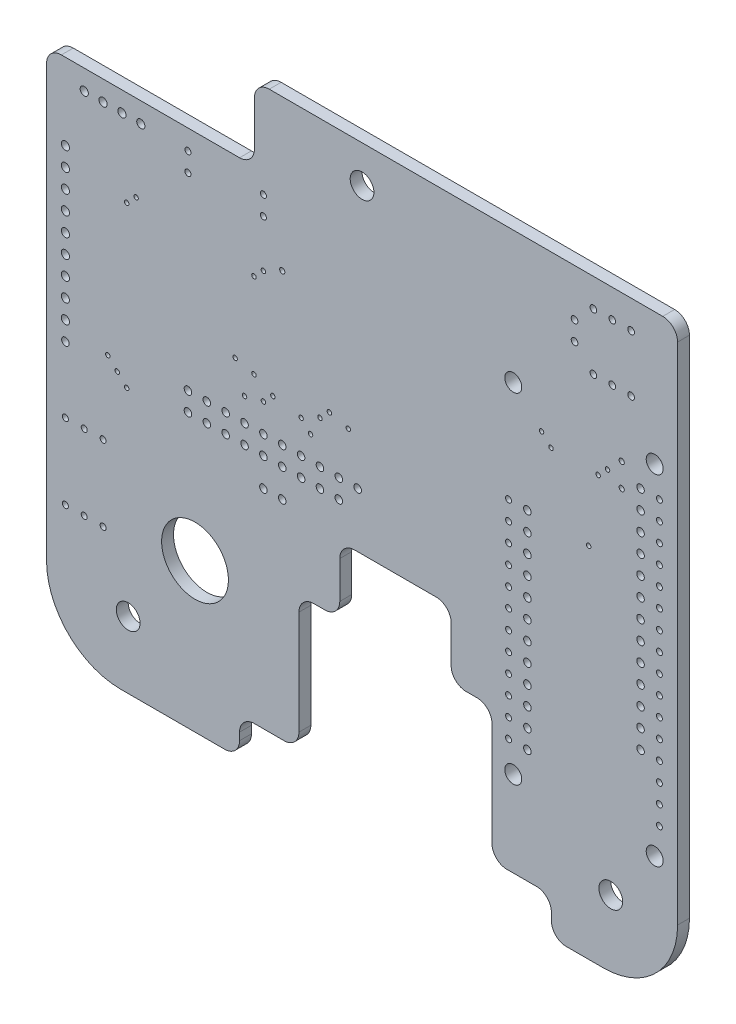
SolidWorks part; units mm, degrees
material "ABS PC"
ref_plane "Front Plane" through (0, 0, 0) normal (0, 0, 1) x (1, 0, 0)
ref_plane "Top Plane" through (0, 0, 0) normal (0, 1, 0) x (1, 0, 0)
ref_plane "Right Plane" through (0, 0, 0) normal (1, 0, 0) x (0, 0, -1)
sketch "20" plane through (0, 0, 0) normal (0, 0, 1) x (1, 0, 0)
  line L0 (28, 72) -> (28, 78)
  line L1 (85, 78) -> (85, 10)
  line L2 (68, 2) -> (68, 3)
  line L3 (66, 5) -> (62, 5)
  line L4 (60, 7) -> (60, 21)
  line L5 (56.5, 23) -> (58, 23)
  line L6 (54.5, 30) -> (54.5, 25)
  line L7 (52.5, 32) -> (41.5, 32)
  line L8 (39.5, 30) -> (39.5, 25)
  line L9 (37.5, 23) -> (36, 23)
  line L10 (34, 21) -> (34, 7)
  line L11 (32, 5) -> (28, 5)
  line L12 (26, 3) -> (26, 2)
  line L13 (0, 68) -> (0, 10)
  line L14 (2, 70) -> (26, 70)
  line L15 (83, 80) -> (30, 80)
  line L16 (10, 0) -> (24, 0)
  line L17 (70, 0) -> (75, 0)
  arc A0 (26, 70) -> (28, 72) centre (26, 72) ccw
  arc A1 (30, 80) -> (28, 78) centre (30, 78) ccw
  arc A2 (85, 78) -> (83, 80) centre (83, 78) ccw
  arc A3 (75, 0) -> (85, 10) centre (75, 10) ccw
  arc A4 (68, 2) -> (70, 0) centre (70, 2) ccw
  arc A5 (68, 3) -> (66, 5) centre (66, 3) ccw
  arc A6 (60, 7) -> (62, 5) centre (62, 7) ccw
  arc A7 (60, 21) -> (58, 23) centre (58, 21) ccw
  arc A8 (54.5, 25) -> (56.5, 23) centre (56.5, 25) ccw
  arc A9 (54.5, 30) -> (52.5, 32) centre (52.5, 30) ccw
  arc A10 (41.5, 32) -> (39.5, 30) centre (41.5, 30) ccw
  arc A11 (37.5, 23) -> (39.5, 25) centre (37.5, 25) ccw
  arc A12 (36, 23) -> (34, 21) centre (36, 21) ccw
  arc A13 (32, 5) -> (34, 7) centre (32, 7) ccw
  arc A14 (28, 5) -> (26, 3) centre (28, 3) ccw
  arc A15 (24, 0) -> (26, 2) centre (24, 2) ccw
  arc A16 (0, 10) -> (10, 0) centre (10, 10) ccw
  arc A17 (2, 70) -> (0, 68) centre (2, 68) ccw
  circle A18 centre (42.5, 75) radius 1.6
  circle A19 centre (11, 9) radius 1.6
  circle A20 centre (76, 9) radius 1.6
  circle A21 centre (62.865, 62.23) radius 1.143
  circle A22 centre (62.865, 16.51) radius 1.143
  circle A23 centre (81.915, 16.51) radius 1.143
  circle A24 centre (81.915, 62.23) radius 1.143
  circle A25 centre (11, 9) radius 0.8 construction
  circle A26 centre (76, 9) radius 0.8 construction
  circle A27 centre (20, 20) radius 4.5
sketch "44" plane through (0, 0, 0) normal (0, 0, 1) x (1, 0, 0)
  circle A0 centre (31.75, 33.02) radius 0.508
  circle A1 centre (29.21, 33.02) radius 0.508
  circle A2 centre (41.91, 39.37) radius 0.508
  circle A3 centre (2.54, 36.83) radius 0.508
  circle A4 centre (80.01, 58.42) radius 0.508
  circle A5 centre (80.01, 27.94) radius 0.508
  circle A6 centre (80.01, 30.48) radius 0.508
  circle A7 centre (80.01, 33.02) radius 0.508
  circle A8 centre (80.01, 35.56) radius 0.508
  circle A9 centre (80.01, 38.1) radius 0.508
  circle A10 centre (80.01, 40.64) radius 0.508
  circle A11 centre (80.01, 43.18) radius 0.508
  circle A12 centre (80.01, 45.72) radius 0.508
  circle A13 centre (80.01, 48.26) radius 0.508
  circle A14 centre (80.01, 50.8) radius 0.508
  circle A15 centre (80.01, 53.34) radius 0.508
  circle A16 centre (80.01, 55.88) radius 0.508
  circle A17 centre (64.77, 48.26) radius 0.508
  circle A18 centre (64.77, 45.72) radius 0.508
  circle A19 centre (64.77, 43.18) radius 0.508
  circle A20 centre (64.77, 40.64) radius 0.508
  circle A21 centre (64.77, 38.1) radius 0.508
  circle A22 centre (64.77, 35.56) radius 0.508
  circle A23 centre (64.77, 33.02) radius 0.508
  circle A24 centre (64.77, 30.48) radius 0.508
  circle A25 centre (64.77, 27.94) radius 0.508
  circle A26 centre (64.77, 25.4) radius 0.508
  circle A27 centre (64.77, 22.86) radius 0.508
  circle A28 centre (64.77, 20.32) radius 0.508
  circle A29 centre (19.05, 36.83) radius 0.508
  circle A30 centre (19.05, 39.37) radius 0.508
  circle A31 centre (21.59, 36.83) radius 0.508
  circle A32 centre (21.59, 39.37) radius 0.508
  circle A33 centre (24.13, 36.83) radius 0.508
  circle A34 centre (24.13, 39.37) radius 0.508
  circle A35 centre (26.67, 36.83) radius 0.508
  circle A36 centre (26.67, 39.37) radius 0.508
  circle A37 centre (29.21, 36.83) radius 0.508
  circle A38 centre (29.21, 39.37) radius 0.508
  circle A39 centre (78.74, 76.2) radius 0.45
  circle A40 centre (71.12, 71.12) radius 0.45
  circle A41 centre (71.12, 73.66) radius 0.45
  circle A42 centre (76.2, 76.2) radius 0.45
  circle A43 centre (78.74, 68.58) radius 0.45
  circle A44 centre (76.2, 68.58) radius 0.45
  circle A45 centre (73.66, 68.58) radius 0.45
  circle A46 centre (73.66, 76.2) radius 0.45
  circle A47 centre (31.75, 36.83) radius 0.508
  circle A48 centre (31.75, 39.37) radius 0.508
  circle A49 centre (34.29, 36.83) radius 0.508
  circle A50 centre (34.29, 39.37) radius 0.508
  circle A51 centre (36.83, 36.83) radius 0.508
  circle A52 centre (36.83, 39.37) radius 0.508
  circle A53 centre (39.37, 36.83) radius 0.508
  circle A54 centre (39.37, 39.37) radius 0.508
  circle A55 centre (2.54, 27.94) radius 0.4064
  circle A56 centre (2.54, 17.78) radius 0.4064
  circle A57 centre (5.08, 27.94) radius 0.4064
  circle A58 centre (5.08, 17.78) radius 0.4064
  circle A59 centre (7.62, 27.94) radius 0.4064
  circle A60 centre (7.62, 17.78) radius 0.4064
  circle A61 centre (29.21, 64.77) radius 0.4064
  circle A62 centre (19.05, 64.77) radius 0.4064
  circle A63 centre (29.21, 67.31) radius 0.4064
  circle A64 centre (19.05, 67.31) radius 0.4064
  circle A65 centre (82.55, 55.88) radius 0.4
  circle A66 centre (82.55, 48.26) radius 0.4
  circle A67 centre (62.23, 48.26) radius 0.4
  circle A68 centre (82.55, 20.32) radius 0.4
  circle A69 centre (62.23, 45.72) radius 0.4
  circle A70 centre (82.55, 50.8) radius 0.4
  circle A71 centre (62.23, 30.48) radius 0.4
  circle A72 centre (62.23, 25.4) radius 0.4
  circle A73 centre (62.23, 20.32) radius 0.4
  circle A74 centre (62.23, 22.86) radius 0.4
  circle A75 centre (62.23, 38.1) radius 0.4
  circle A76 centre (62.23, 35.56) radius 0.4
  circle A77 centre (62.23, 40.64) radius 0.4
  circle A78 centre (62.23, 33.02) radius 0.4
  circle A79 centre (62.23, 27.94) radius 0.4
  circle A80 centre (82.55, 27.94) radius 0.4
  circle A81 centre (82.55, 30.48) radius 0.4
  circle A82 centre (82.55, 53.34) radius 0.4
  circle A83 centre (82.55, 45.72) radius 0.4
  circle A84 centre (82.55, 43.18) radius 0.4
  circle A85 centre (82.55, 40.64) radius 0.4
  circle A86 centre (82.55, 38.1) radius 0.4
  circle A87 centre (82.55, 35.56) radius 0.4
  circle A88 centre (82.55, 58.42) radius 0.4
  circle A89 centre (82.55, 25.4) radius 0.4
  circle A90 centre (82.55, 33.02) radius 0.4
  circle A91 centre (82.55, 22.86) radius 0.4
  circle A92 centre (62.23, 43.18) radius 0.4
  circle A93 centre (7.62, 67.31) radius 0.55
  circle A94 centre (2.54, 39.37) radius 0.55
  circle A95 centre (2.54, 59.69) radius 0.55
  circle A96 centre (2.54, 57.15) radius 0.55
  circle A97 centre (2.54, 54.61) radius 0.55
  circle A98 centre (2.54, 52.07) radius 0.55
  circle A99 centre (2.54, 49.53) radius 0.55
  circle A100 centre (2.54, 46.99) radius 0.55
  circle A101 centre (2.54, 44.45) radius 0.55
  circle A102 centre (2.54, 41.91) radius 0.55
  circle A103 centre (12.7, 67.31) radius 0.55
  circle A104 centre (10.16, 67.31) radius 0.55
  circle A105 centre (5.08, 67.31) radius 0.55
  circle A106 centre (77.47, 60.325) radius 0.35
  circle A107 centre (77.47, 57.15) radius 0.35
  circle A108 centre (31.75, 59.69) radius 0.35
  circle A109 centre (73.025, 48.26) radius 0.3
  circle A110 centre (8.255, 38.1) radius 0.3
  circle A111 centre (26.67, 42.545) radius 0.3
  circle A112 centre (29.21, 43.18) radius 0.3
  circle A113 centre (30.48, 44.45) radius 0.3
  circle A114 centre (27.94, 45.72) radius 0.3
  circle A115 centre (25.4, 46.355) radius 0.3
  circle A116 centre (35.56, 42.545) radius 0.3
  circle A117 centre (34.29, 43.815) radius 0.3
  circle A118 centre (9.525, 36.83) radius 0.3
  circle A119 centre (40.64, 45.72) radius 0.3
  circle A120 centre (36.83, 45.085) radius 0.3
  circle A121 centre (10.795, 35.56) radius 0.3
  circle A122 centre (38.1, 46.355) radius 0.3
  circle A123 centre (75.565, 58.42) radius 0.3
  circle A124 centre (29.21, 58.42) radius 0.3
  circle A125 centre (12.065, 58.42) radius 0.3
  circle A126 centre (66.675, 58.42) radius 0.3
  circle A127 centre (74.295, 57.15) radius 0.3
  circle A128 centre (27.94, 57.15) radius 0.3
  circle A129 centre (10.795, 57.15) radius 0.3
  circle A130 centre (67.945, 57.15) radius 0.3
extrude "Boss-Extrude1" add sketch "20" along normal blind 1.6
extrude "Cut-Extrude2" cut sketch "44" along normal through all
ref_plane "Plane1" through (47, 0, 0) normal (-1, 0, 0) x (0, 0, 1)
ref_plane "Plane2" through (42.5, 0, 0) normal (1, 0, 0) x (0, 0, -1)
